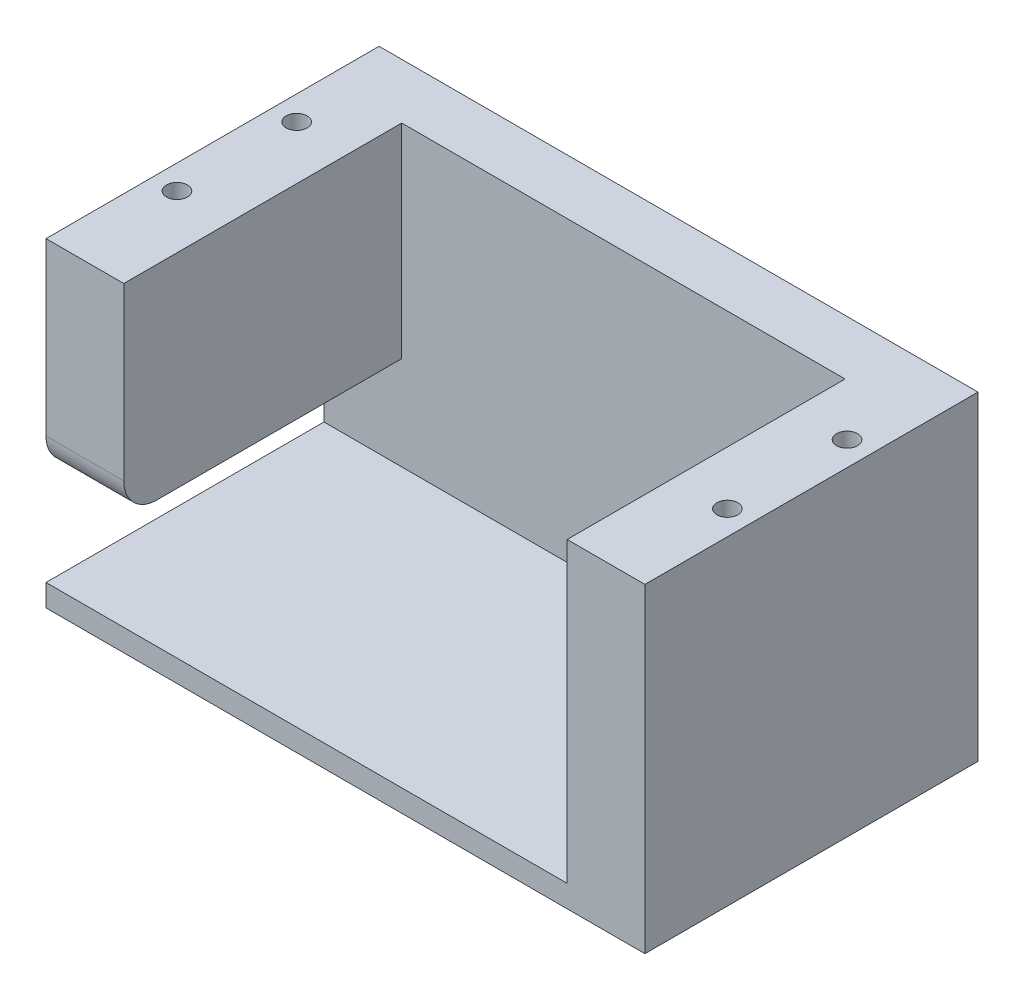
SolidWorks part; units mm, degrees
ref_plane "Front Plane" through (0, 0, 0) normal (0, 0, 1) x (1, 0, 0)
ref_plane "Top Plane" through (0, 0, 0) normal (0, 1, 0) x (1, 0, 0)
ref_plane "Right Plane" through (0, 0, 0) normal (1, 0, 0) x (0, 0, -1)
sketch "Sketch1" plane through (0, 0, 0) normal (0, 1, 0) x (1, 0, 0)
  line L0 (0, -2.75) -> (0, 2.75) construction
  line L1 (-22.15, -10.1) -> (22.15, -10.1) construction
  line L2 (-22.15, -10.1) -> (-22.15, 10.1) construction
  line L3 (-22.15, 10.1) -> (22.15, 10.1) construction
  line L4 (22.15, -10.1) -> (22.15, 10.1) construction
  line L5 (-22.15, -10.1) -> (22.15, 10.1) construction
  line L6 (-22.15, 10.1) -> (22.15, -10.1) construction
  line L7 (-22.15, 10.1) -> (-27.15, 10.1) construction
  line L8 (-22.15, 10.1) -> (-22.15, -10.1) construction
  line L9 (-22.15, -10.1) -> (-27.15, -10.1) construction
  line L10 (-27.15, 10.1) -> (-27.15, -10.1)
  line L11 (27.15, 10.1) -> (27.15, -10.1)
  line L12 (22.15, -10.1) -> (27.15, -10.1) construction
  line L13 (22.15, 10.1) -> (27.15, 10.1) construction
  line L14 (-2.75, 0) -> (2.75, 0) construction
  line L15 (-27.15, 10.1) -> (27.15, 10.1) construction
  line L16 (-27.15, 10.1) -> (-27.15, 15.1)
  line L17 (-27.15, 15.1) -> (27.15, 15.1)
  line L18 (27.15, 10.1) -> (27.15, 15.1)
  line L19 (-27.15, -15.1) -> (27.15, -15.1)
  line L20 (27.15, -10.1) -> (27.15, -15.1)
  line L21 (-27.15, -10.1) -> (27.15, -10.1) construction
  line L22 (-27.15, -10.1) -> (-27.15, -15.1)
  point P0 (0, 0)
  dimension "D1" = 44.3
  dimension "D2" = 20.2
  dimension "D3" = 5
  dimension "D4" = 5
extrude "Boss-Extrude1" add sketch "Sketch1" along normal blind 2
sketch "Sketch7" plane through (0, 2, 0) normal (0, 1, 0) x (1, 0, 0)
  line L1 (-20.1, -10.1) -> (20.1, -10.1)
  line L2 (-20.1, -10.1) -> (-20.1, 10.1)
  line L3 (-20.1, 10.1) -> (20.1, 10.1)
  line L4 (20.1, -10.1) -> (20.1, 10.1)
  line L5 (-20.1, -10.1) -> (20.1, 10.1) construction
  line L6 (-20.1, 10.1) -> (20.1, -10.1) construction
  point P0 (0, 0)
  dimension "D1" = 20.2
  dimension "D2" = 40.2
extrude "Boss-Extrude3" add sketch "Sketch7" along normal blind 27
sketch "Sketch8" plane through (0, 29, 0) normal (0, 1, 0) x (1, 0, 0)
  line L1 (-20.1, -10.1) -> (20.1, -10.1)
  line L2 (-20.1, -10.1) -> (-20.1, -15.1)
  line L3 (-20.1, -15.1) -> (20.1, -15.1)
  line L4 (20.1, -10.1) -> (20.1, -15.1)
  line L5 (20.1, -10.1) -> (20.1, 10.1) construction
  line L7 (-20.1, -10.1) -> (-20.1, 10.1) construction
extrude "Cut-Extrude2" cut sketch "Sketch8" against normal up to surface (27 mm away) contours L2 L1 L4 L3 up to face at (0, 2, 0)
sketch "Sketch9" plane through (-22.15, 0, 0) normal (1, 0, 0) x (0, 0, -1)
  line L1 (-15.1, 10.5) -> (10.1, 10.5)
  line L2 (-15.1, 10.5) -> (-15.1, 2)
  line L3 (-15.1, 2) -> (10.1, 2)
  line L4 (10.1, 10.5) -> (10.1, 2)
  point P4 (0, 0)
  point P8 (0, 0)
  point P9 (0, 0)
  dimension "D1" = 8.5
extrude "Cut-Extrude3" cut sketch "Sketch9" against normal up to next contours L2 L1 L4 L3
sketch "Sketch10" plane through (0, 29, 0) normal (0, 1, 0) x (1, 0, 0)
  line L0 (-22.15, 0) -> (-27.15, 0) construction
  line L1 (27.15, 0) -> (-27.15, 0) construction
  line L2 (27.15, -15.1) -> (27.15, 15.1) construction
  line L3 (0, -13.5924) -> (0, -0.9924) construction
  line L4 (-27.15, 15.1) -> (-27.15, -15.1) construction
  circle A0 centre (-24.95, -5.425) radius 2.8 construction
  circle A1 centre (-24.95, -5.425) radius 0.95
  circle A2 centre (-24.95, 5.425) radius 0.95
  circle A3 centre (24.95, -5.425) radius 0.95
  circle A4 centre (24.95, 5.425) radius 0.95
  dimension "D1" = 5.6
  dimension "D2" = 22.15
  dimension "D3" = 2.625
  dimension "D4" = 1.9
extrude "Cut-Extrude4" cut sketch "Sketch10" against normal blind 10
fillet "Fillet1" radius 3 1 edges at (-24.65, 10.5, 15.1)
sketch "Sketch12" plane through (-20.1, 0, 0) normal (1, 0, 0) x (0, 0, -1)
  line L4 (-15.1, 2) -> (10.1, 2)
  line L5 (-15.1, 13.5) -> (-15.1, 2)
  line L6 (10.1, 10.5) -> (-12.1, 10.5)
  line L7 (10.1, 2) -> (10.1, 10.5)
  line L8 (-15.1, 2) -> (10.1, 2)
  line L9 (-15.1, 13.5) -> (-15.1, 2)
  line L10 (10.1, 10.5) -> (-12.1, 10.5)
  line L11 (10.1, 2) -> (10.1, 10.5)
  arc A1 (-15.1, 13.5) -> (-12.1, 10.5) centre (-12.1, 13.5) ccw
  arc A2 (-15.1, 13.5) -> (-12.1, 10.5) centre (-12.1, 13.5) ccw
  dimension "D1" = 0
extrude "Cut-Extrude5" cut sketch "Sketch12" against normal up to next
